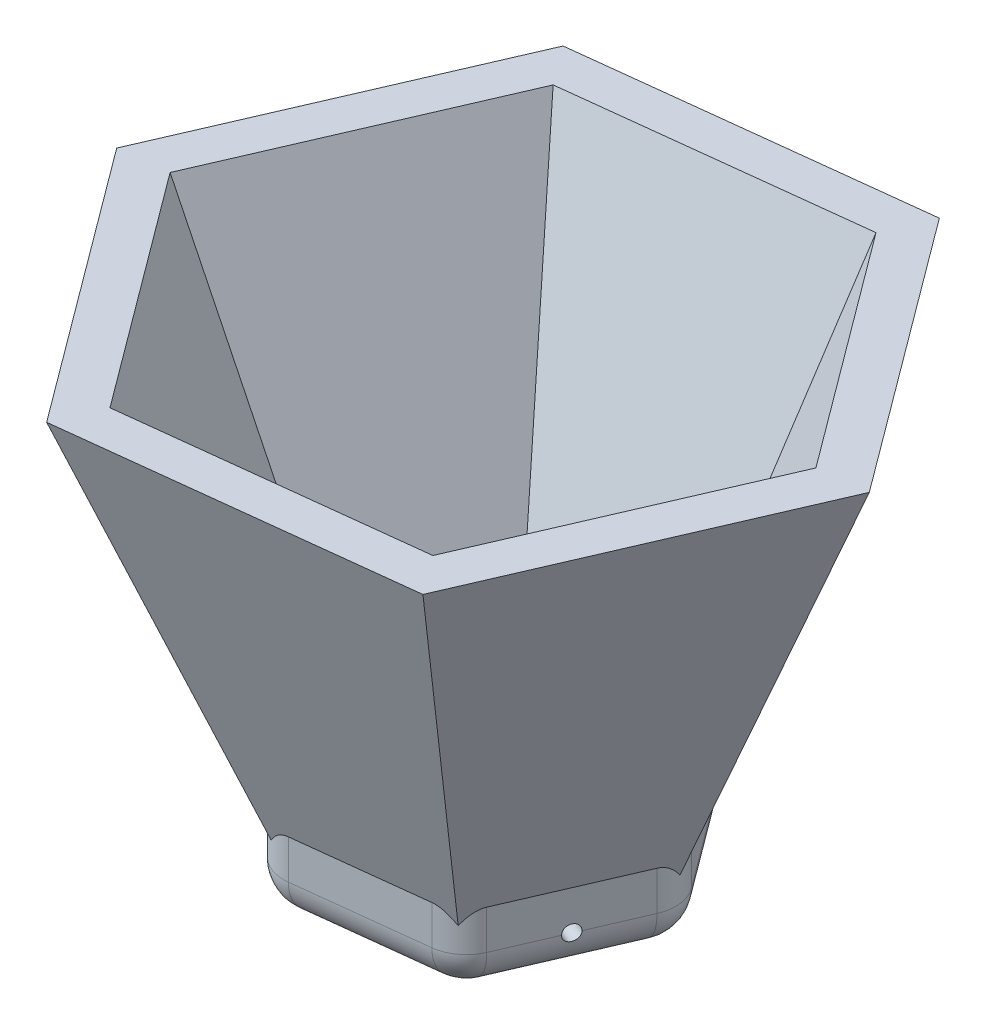
SolidWorks part; units mm, degrees
ref_plane "Front Plane" through (0, 0, 0) normal (0, 0, 1) x (1, 0, 0)
ref_plane "Top Plane" through (0, 0, 0) normal (0, 1, 0) x (1, 0, 0)
ref_plane "Right Plane" through (0, 0, 0) normal (1, 0, 0) x (0, 0, -1)
sketch "Sketch3" plane through (0, 0, 0) normal (0, 1, 0) x (1, 0, 0)
  line L1 (43.0136, 4.9829) -> (17.1914, 39.7423)
  line L2 (17.1914, 39.7423) -> (-25.8222, 34.7594)
  line L8 (-25.8222, 34.7594) -> (-43.0136, -4.9829)
  line L9 (-43.0136, -4.9829) -> (-17.1914, -39.7423)
  line L10 (-17.1914, -39.7423) -> (25.8222, -34.7594)
  line L11 (25.8222, -34.7594) -> (43.0136, 4.9829)
  circle A0 centre (0, 0) radius 37.5 construction
extrude "Boss-Extrude1" add sketch "Sketch3" against normal blind 50 draft 20
shell "Shell3" thickness 5
sketch "Sketch9" plane through (0, 0, 0) normal (0, 1, 0) x (1, 0, 0)
  line L0 (0, 19.9173) -> (0, -19.9173)
  arc A0 (0, 19.9173) -> (0, -19.9173) centre (0, 0) ccw
  point P6 (0, 0)
revolve "Revolve1" [suppressed] add sketch "Sketch9" angle 360 about L0
sketch "Sketch11" plane through (0, -50, 0) normal (0, -1, 0) x (1, 0, 0)
  line L1 (13.2908, 17.8909) -> (-8.8485, 20.4556)
  line L2 (-8.8485, 20.4556) -> (-22.1394, 2.5648)
  line L3 (-22.1394, 2.5648) -> (-13.2908, -17.8909)
  line L4 (-13.2908, -17.8909) -> (8.8485, -20.4556)
  line L5 (8.8485, -20.4556) -> (22.1394, -2.5648)
  line L6 (22.1394, -2.5648) -> (13.2908, 17.8909)
  circle A0 centre (0, 0) radius 19.3015 construction
extrude "Boss-Extrude3" add sketch "Sketch11" along normal blind 10
sketch "Sketch12" plane through (-17.7151, 0, -7.6631) normal (-0.9178, 0, -0.397) x (-0.397, 0, 0.9178)
  line L0 (-11.1437, -50) -> (11.1437, -50) construction
  circle A0 centre (0, -55) radius 1
  dimension "D1" = 5
fillet "Fillet2" radius 5 12 edges at (17.7151, -60, 7.6631) (15.494, -60, -11.5102) (-2.2211, -60, -19.1733) (-17.7151, -60, -7.6631) (-15.494, -60, 11.5102) (2.2211, -60, 19.1733) (-8.8485, -55, 20.4556) (13.2908, -55, 17.8909) (22.1394, -55, -2.5648) (8.8485, -55, -20.4556) (-13.2908, -55, -17.8909) (-22.1394, -55, 2.5648)
extrude "Cut-Extrude1" cut sketch "Sketch12" against normal through all contours A0
